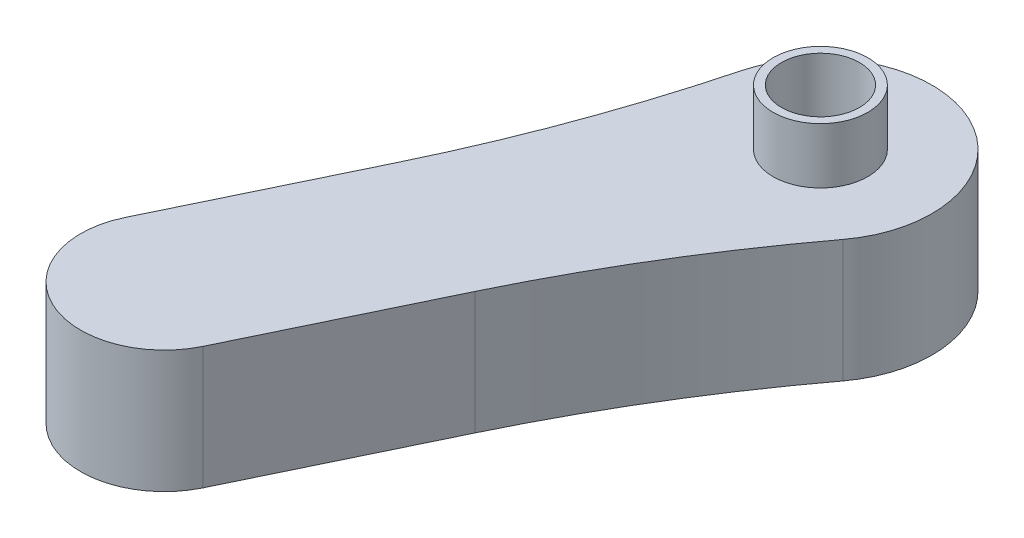
SolidWorks part; units mm, degrees
ref_plane "前视基准面" through (0, 0, 0) normal (0, 0, 1) x (1, 0, 0)
ref_plane "上视基准面" through (0, 0, 0) normal (0, 1, 0) x (1, 0, 0)
ref_plane "右视基准面" through (0, 0, 0) normal (1, 0, 0) x (0, 0, -1)
other "Configuration Table"
sketch "草图1" plane through (0, 0, 0) normal (0, 1, 0) x (1, 0, 0)
  line L0 (-24.6821, 11.889) -> (45039.2818, -21694.7726) construction
  line L1 (437.4366, 908.1372) -> (0, 0) construction
  line L2 (-71.9176, -80.174) -> (-103.6043, -145.9569)
  line L4 (-17.8618, -106.2118) -> (-49.5485, -171.9948)
  line L5 (-89.5953, -186.0037) -> (-21694.7726, -45039.2818) construction
  arc A0 (32.0447, -23.9403) -> (-38.695, 10.134) centre (0, 0) ccw
  arc A1 (-103.6043, -145.9569) -> (-49.5485, -171.9948) centre (-76.5764, -158.9758) ccw
  arc A2 (-17.8618, -106.2118) -> (32.0447, -23.9403) centre (432.6031, -323.1943) cw
  arc A3 (-71.9176, -80.174) -> (-38.695, 10.134) centre (-522.3825, 136.8085) ccw
  point P12 (-76.5764, -158.9758)
  point P18 (15.5463, -36.8553)
  point P21 (-38.5095, -10.8174)
  dimension "D1" = 80
  dimension "D4" = 500
  dimension "D2" = 30
  dimension "D3" = 150
extrude "凸台-拉伸1" add sketch "草图1" along normal blind 4
sketch "草图4" plane through (0, 4, 0) normal (0, 1, 0) x (1, 0, 0)
  circle A0 centre (0, 0) radius 17
  circle A1 centre (0, 0) radius 14
  dimension "D1" = 34
  dimension "D2" = 28
extrude "凸台-拉伸2" add sketch "草图4" along normal blind 20
sketch "草图5" plane through (0, 4, 0) normal (0, 1, 0) x (1, 0, 0)
  circle A0 centre (3.4717, 7.2074) radius 1.75
  circle A1 centre (7.2074, -3.4717) radius 1.75
  circle A2 centre (-3.4717, -7.2074) radius 1.75
  circle A3 centre (-7.2074, 3.4717) radius 1.75
  point P12 (0, 0)
  dimension "D1" = 3.5
  dimension "D2" = 4
extrude "切除-拉伸1" cut sketch "草图5" against normal blind 20
sketch "草图6" plane through (0, 0, 0) normal (0, -1, 0) x (1, 0, 0)
  circle A0 centre (-3.4717, 7.2074) radius 2.4
  circle A1 centre (7.2074, 3.4717) radius 2.4
  circle A2 centre (3.4717, -7.2074) radius 2.4
  circle A3 centre (-7.2074, -3.4717) radius 2.4
  point P12 (0, 0)
  dimension "D1" = 4.8
  dimension "D2" = 4
extrude "切除-拉伸2" cut sketch "草图6" against normal blind 3
sketch "草图11" plane through (0, 0, 0) normal (0, -1, 0) x (1, 0, 0)
  line L5 (-103.6043, 145.9569) -> (-71.9176, 80.174)
  line L6 (-17.8618, 106.2118) -> (-49.5485, 171.9948)
  line L7 (-100.0005, 147.6927) -> (-68.3139, 81.9098)
  line L8 (-21.4655, 104.476) -> (-53.1522, 170.2589)
  line L9 (-96.7458, 140.9358) -> (-71.5686, 88.6668)
  line L10 (-24.7202, 111.233) -> (-49.8975, 163.5019)
  line L11 (-100.0005, 147.6927) -> (-68.3139, 81.9098) construction
  line L12 (0, 0) -> (-21698.2444, 45046.4892) construction
  line L13 (-21.4655, 104.476) -> (-53.1522, 170.2589) construction
  arc A16 (-38.695, -10.134) -> (-71.9176, 80.174) centre (-522.3825, -136.8085) ccw
  arc A17 (-38.695, -10.134) -> (32.0447, 23.9403) centre (0, 0) ccw
  arc A18 (-17.8618, 106.2118) -> (32.0447, 23.9403) centre (432.6031, 323.1943) ccw
  arc A19 (-49.5485, 171.9948) -> (-103.6043, 145.9569) centre (-76.5764, 158.9758) ccw
  arc A20 (-53.1522, 170.2589) -> (-100.0005, 147.6927) centre (-76.5764, 158.9758) ccw
  arc A21 (-21.4655, 104.476) -> (28.8402, 21.5463) centre (432.6031, 323.1943) ccw
  arc A22 (-34.8255, -9.1206) -> (28.8402, 21.5463) centre (0, 0) ccw
  arc A23 (-34.8255, -9.1206) -> (-68.3139, 81.9098) centre (-522.3825, -136.8085) ccw
  arc A24 (-57.3475, 176.4758) -> (-102.2467, 154.8485) centre (-76.5764, 158.9758) ccw
  arc A25 (-18.1606, 97.7434) -> (24.3962, 27.5879) centre (432.6031, 323.1943) ccw
  arc A26 (-32.18, -16.1385) -> (8.5635, -34.9667) centre (0, 0) ccw
  arc A27 (-36.7795, -1.8796) -> (-65.1095, 75.1288) centre (-522.3825, -136.8085) ccw
  arc A28 (22.0039, -28.4926) -> (8.5635, -34.9667) centre (15.6227, -32.4335) ccw
  arc A29 (-32.18, -16.1385) -> (-36.7795, -1.8796) centre (-34.8255, -9.1206) ccw
  arc A30 (-65.1095, 75.1288) -> (-71.5686, 88.6668) centre (-68.3139, 81.9098) ccw
  arc A31 (-96.7458, 140.9358) -> (-102.2467, 154.8485) centre (-100.0005, 147.6927) ccw
  arc A32 (22.0039, -28.4926) -> (32.6787, 15.103) centre (0, 0) ccw
  arc A33 (-34.8255, -9.1206) -> (28.8402, 21.5463) centre (0, 0) ccw construction
  arc A34 (-34.8255, -9.1206) -> (-68.3139, 81.9098) centre (-522.3825, -136.8085) ccw construction
  arc A35 (-53.1522, 170.2589) -> (-100.0005, 147.6927) centre (-76.5764, 158.9758) ccw construction
  arc A36 (32.6787, 15.103) -> (24.3962, 27.5879) centre (28.8402, 21.5463) cw
  arc A37 (-18.1606, 97.7434) -> (-24.7202, 111.233) centre (-21.4655, 104.476) cw
  arc A38 (-49.8975, 163.5019) -> (-57.3475, 176.4758) centre (-53.1522, 170.2589) cw
  arc A39 (-21.4655, 104.476) -> (28.8402, 21.5463) centre (432.6031, 323.1943) ccw construction
  dimension "D3" = 15
  dimension "D4" = 15
  dimension "D5" = 15
  dimension "D6" = 15
  dimension "D1" = 4
  dimension "D2" = 4
extrude "凸台-拉伸5" add sketch "草图11" along normal blind 40
sketch "草图12" plane through (0, -40, 0) normal (0, -1, 0) x (1, 0, 0)
  line L0 (0, 0) -> (-21698.2444, 45046.4892) construction
  circle A0 centre (27.5687, 20.7504) radius 2.4
  arc A1 (24.3962, 27.5879) -> (32.6787, 15.103) centre (28.8402, 21.5463) ccw construction
  circle A2 centre (-22.8224, 103.8366) radius 2.4
  circle A3 centre (-54.5085, 169.6183) radius 2.4
  circle A4 centre (14.9718, -31.0821) radius 2.4
  arc A5 (22.0039, -28.4926) -> (8.5635, -34.9667) centre (15.6227, -32.4335) ccw construction
  arc A6 (-57.3475, 176.4758) -> (-102.2467, 154.8485) centre (-76.5764, 158.9758) ccw construction
  arc A7 (-24.7202, 111.233) -> (-18.1606, 97.7434) centre (-21.4655, 104.476) ccw construction
  arc A8 (-57.3475, 176.4758) -> (-49.8975, 163.5019) centre (-53.1522, 170.2589) ccw construction
  circle A9 centre (-98.6541, 148.354) radius 2.4
  circle A10 centre (-66.9681, 82.5722) radius 2.4
  circle A11 centre (-33.4106, -8.6225) radius 2.4
  point P31 (-87.8595, 182.4)
  dimension "D1" = 1.5
  dimension "D2" = 4.8
  dimension "D3" = 4.8
  dimension "D4" = 1.5
  dimension "D5" = 1.5
  dimension "D6" = 4.8
  dimension "D7" = 4.8
  dimension "D8" = 1.5
extrude "切除-拉伸3" cut sketch "草图12" against normal blind 3
